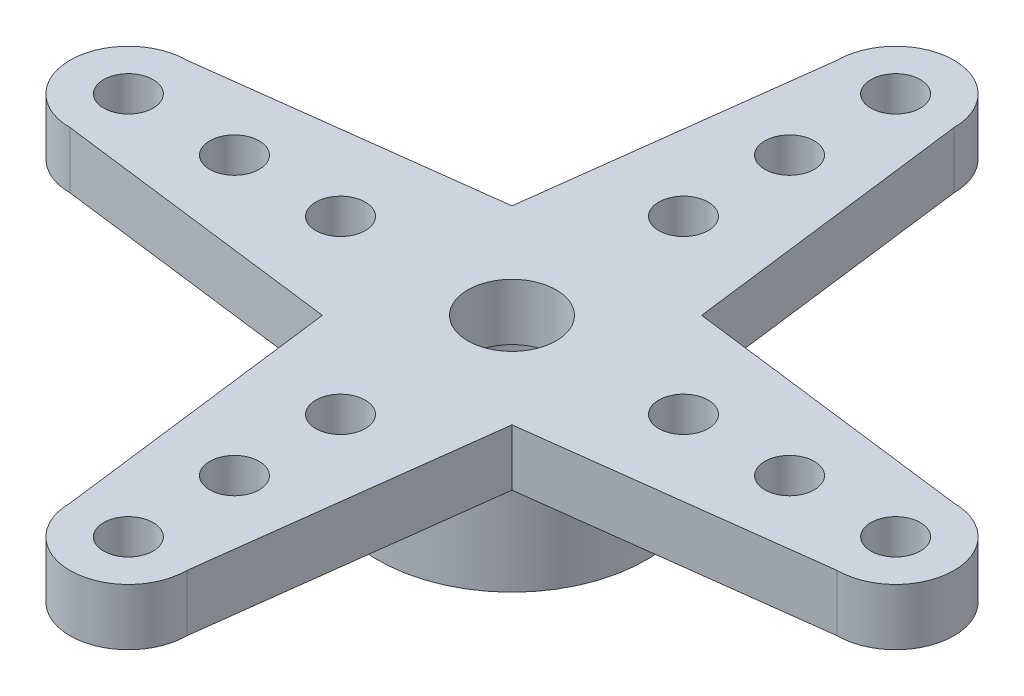
SolidWorks part; units mm, degrees
ref_plane "Front Plane" through (0, 0, 0) normal (0, 0, 1) x (1, 0, 0)
ref_plane "Top Plane" through (0, 0, 0) normal (0, 1, 0) x (1, 0, 0)
ref_plane "Right Plane" through (0, 0, 0) normal (1, 0, 0) x (0, 0, -1)
sketch "Sketch1" plane through (0, 0, 0) normal (0, 1, 0) x (1, 0, 0)
  line L0 (-12.5, 0) -> (12.5, 0) construction
  line L1 (0, 12.5) -> (0, -12.5) construction
  line L2 (-10.8472, -1.6503) -> (-2.6819, -2.6819)
  line L3 (-2.6819, -2.6819) -> (-1.6503, -10.8472)
  line L4 (1.6503, -10.8472) -> (2.6819, -2.6819)
  line L5 (2.6819, -2.6819) -> (10.8472, -1.6503)
  line L6 (10.8472, 1.6503) -> (2.6819, 2.6819)
  line L7 (2.6819, 2.6819) -> (1.6503, 10.8472)
  line L8 (-1.6503, 10.8472) -> (-2.6819, 2.6819)
  line L9 (-2.6819, 2.6819) -> (-10.8472, 1.6503)
  line L10 (-10.8497, 0) -> (-7.8497, 0) construction
  arc A0 (-10.8472, -1.6503) -> (-10.8472, 1.6503) centre (-10.8497, 0) cw
  arc A1 (-1.6503, -10.8472) -> (1.6503, -10.8472) centre (0, -10.8497) ccw
  arc A2 (10.8472, -1.6503) -> (10.8472, 1.6503) centre (10.8497, 0) ccw
  arc A3 (-1.6503, 10.8472) -> (1.6503, 10.8472) centre (0, 10.8497) cw
  circle A4 centre (0, 4.8497) radius 0.7
  circle A5 centre (0, 7.8497) radius 0.7
  circle A6 centre (0, 10.8497) radius 0.7
  circle A7 centre (0, -4.8497) radius 0.7
  circle A8 centre (0, -7.8497) radius 0.7
  circle A9 centre (0, -10.8497) radius 0.7
  circle A10 centre (-10.8497, 0) radius 0.7
  circle A11 centre (-7.8497, 0) radius 0.7
  circle A12 centre (-4.8497, 0) radius 0.7
  circle A13 centre (10.8497, 0) radius 0.7
  circle A14 centre (4.8497, 0) radius 0.7
  circle A15 centre (7.8497, 0) radius 0.7
  circle A16 centre (0, 0) radius 1.25
  point P4 (0, 0)
  point P8 (0, 0)
  point P21 (-12.5, 0)
  point P25 (0, -12.5)
  point P26 (12.5, 0)
  point P27 (0, 12.5)
  dimension "D2" = 1.4
  dimension "D5" = 1.4
  dimension "D8" = 2.5
  dimension "D1" = 25
  dimension "D3" = 3
  dimension "D4" = 3
  dimension "D7" = 3
  dimension "D6" = 3
extrude "Boss-Extrude1" add sketch "Sketch1" along normal blind 1.6
sketch "Sketch2" plane through (0, 0, 0) normal (0, -1, 0) x (1, 0, 0)
  circle A0 centre (0, 0) radius 2.43
  circle A1 centre (0, 0) radius 3.7928
  dimension "D1" = 4.86
extrude "Boss-Extrude2" add sketch "Sketch2" along normal blind 2.5
